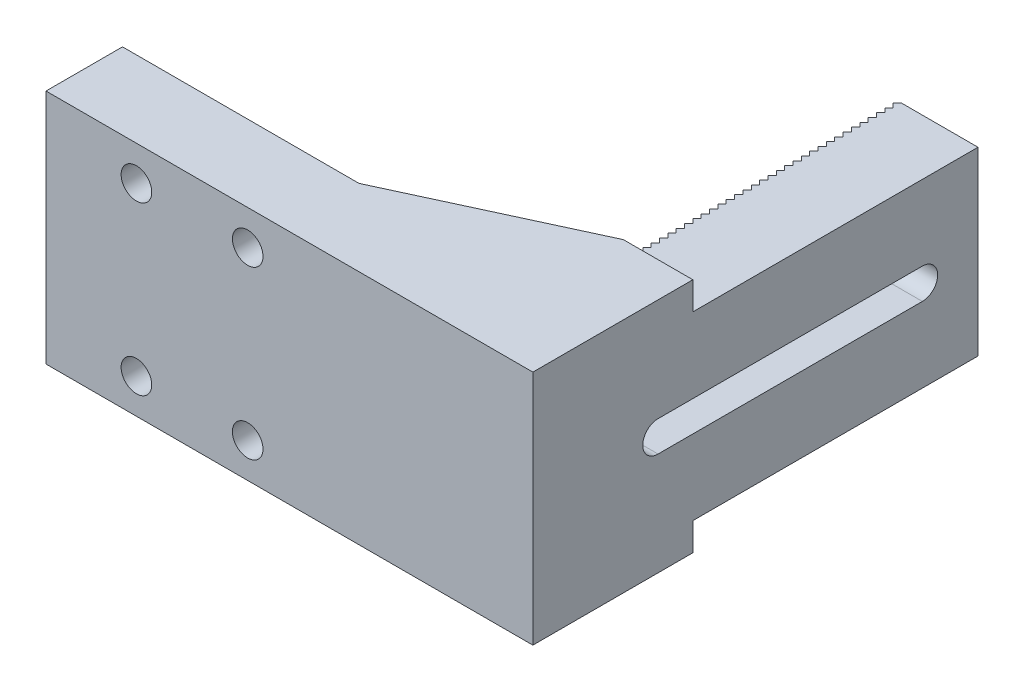
SolidWorks part; units mm, degrees
ref_plane "前视基准面" through (0, 0, 0) normal (0, 0, 1) x (1, 0, 0)
ref_plane "上视基准面" through (0, 0, 0) normal (0, 1, 0) x (1, 0, 0)
ref_plane "右视基准面" through (0, 0, 0) normal (1, 0, 0) x (0, 0, -1)
sketch "草图1" plane through (0, 0, 0) normal (0, 1, 0) x (1, 0, 0)
  line L0 (0, 0) -> (-35, 0)
  line L1 (-35, 0) -> (-35, 5.5)
  line L2 (-35, 5.5) -> (-5, 5.5)
  line L3 (-5, 5.5) -> (-5, 32)
  line L4 (-5, 32) -> (0, 32)
  line L5 (0, 32) -> (0, 0)
  dimension "D1" = 5.5
  dimension "D2" = 5
  dimension "D3" = 35
  dimension "D4" = 32
extrude "凸台-拉伸1" add sketch "草图1" along normal blind 17
sketch "草图4" plane through (0, 0, 0) normal (0, 0, 1) x (1, 0, 0)
  line L0 (-35, 17) -> (-5, 17) construction
  line L1 (-24.5, 27.5741) -> (-24.5, -6.7865) construction
  line L2 (-35, 8.5) -> (-8.9406, 8.5) construction
  line L3 (-35, 17) -> (-35, 0) construction
  line L5 (-5, 17) -> (-5, 0) construction
  circle A0 centre (-28.5, 14.5) radius 1.1
  circle A1 centre (-20.5, 14.5) radius 1.1
  circle A2 centre (-28.5, 2.5) radius 1.1
  circle A3 centre (-20.5, 2.5) radius 1.1
  dimension "D1" = 2.2
  dimension "D2" = 8
  dimension "D3" = 12
  dimension "D5" = 15.5
  dimension "D6" = 2.2
  dimension "D4" = 10.5
extrude "切除-拉伸2" cut sketch "草图4" along direction (0, 0, 1) on the side against the normal through all
sketch "草图8" plane through (-5, 0, 0) normal (-1, 0, 0) x (0, 0, 1)
  line L0 (-32, 15) -> (-11.5, 15)
  line L1 (-32, 17) -> (-32, 0) construction
  line L2 (-11.5, 15) -> (-11.5, 17)
  line L3 (-11.5, 17) -> (-32, 17)
  line L4 (-32, 17) -> (-32, 15)
  line L5 (-32, 8.5) -> (0.3903, 8.5) construction
  line L6 (-11.5, 2) -> (-11.5, 0)
  line L7 (-11.5, 0) -> (-32, 0)
  line L8 (-32, 0) -> (-32, 2)
  line L9 (-32, 2) -> (-11.5, 2)
  line L11 (-32, 17) -> (-5.5, 17) construction
  line L12 (-5.5, 17) -> (-5.5, 0) construction
  point P14 (-11.2961, 15)
  point P15 (-11.2961, 15)
  point P16 (-10.0837, 17)
  point P21 (-10, 15)
  dimension "D2" = 13
  dimension "D3" = 6
extrude "切除-拉伸5" cut sketch "草图8" against normal through all
sketch "草图11" plane through (0, 2, 0) normal (0, -1, 0) x (1, 0, 0)
  line L0 (-5, -5.5) -> (-5, -32)
  line L1 (-5, -32) -> (-5.5, -32)
  line L2 (-5.5, -32) -> (-5.8, -31.7)
  line L3 (-5.8, -31.7) -> (-5.5, -31.4)
  line L29 (-5, -5.5) -> (-35, -5.5) construction
  line L30 (-5.5, -5.5) -> (-5, -5.5)
  line L31 (-5.5, -31.4) -> (-5.8, -31.1)
  line L32 (-5.8, -31.1) -> (-5.5, -30.8)
  line L33 (-5.5, -30.8) -> (-5.8, -30.5)
  line L34 (-5.8, -30.5) -> (-5.5, -30.2)
  line L35 (-5.5, -30.2) -> (-5.8, -29.9)
  line L36 (-5.8, -29.9) -> (-5.5, -29.6)
  line L37 (-5.5, -29.6) -> (-5.8, -29.3)
  line L38 (-5.8, -29.3) -> (-5.5, -29)
  line L39 (-5.5, -29) -> (-5.8, -28.7)
  line L40 (-5.8, -28.7) -> (-5.5, -28.4)
  line L41 (-5.5, -28.4) -> (-5.8, -28.1)
  line L42 (-5.8, -28.1) -> (-5.5, -27.8)
  line L43 (-5.5, -27.8) -> (-5.8, -27.5)
  line L44 (-5.8, -27.5) -> (-5.5, -27.2)
  line L45 (-5.5, -27.2) -> (-5.8, -26.9)
  line L46 (-5.8, -26.9) -> (-5.5, -26.6)
  line L47 (-5.5, -26.6) -> (-5.8, -26.3)
  line L48 (-5.8, -26.3) -> (-5.5, -26)
  line L49 (-5.5, -26) -> (-5.8, -25.7)
  line L50 (-5.8, -25.7) -> (-5.5, -25.4)
  line L51 (-5.5, -25.4) -> (-5.8, -25.1)
  line L52 (-5.8, -25.1) -> (-5.5, -24.8)
  line L53 (-5.5, -24.8) -> (-5.8, -24.5)
  line L54 (-5.8, -24.5) -> (-5.5, -24.2)
  line L55 (-5.5, -24.2) -> (-5.8, -23.9)
  line L56 (-5.8, -23.9) -> (-5.5, -23.6)
  line L57 (-5.5, -23.6) -> (-5.8, -23.3)
  line L58 (-5.8, -23.3) -> (-5.5, -23)
  line L59 (-5.5, -23) -> (-5.8, -22.7)
  line L60 (-5.8, -22.7) -> (-5.5, -22.4)
  line L61 (-5.5, -22.4) -> (-5.8, -22.1)
  line L62 (-5.8, -22.1) -> (-5.5, -21.8)
  line L63 (-5.5, -21.8) -> (-5.8, -21.5)
  line L64 (-5.8, -21.5) -> (-5.5, -21.2)
  line L65 (-5.5, -21.2) -> (-5.8, -20.9)
  line L66 (-5.8, -20.9) -> (-5.5, -20.6)
  line L67 (-5.5, -20.6) -> (-5.8, -20.3)
  line L68 (-5.8, -20.3) -> (-5.5, -20)
  line L69 (-5.5, -20) -> (-5.8, -19.7)
  line L70 (-5.8, -19.7) -> (-5.5, -19.4)
  line L71 (-5.5, -19.4) -> (-5.8, -19.1)
  line L72 (-5.8, -19.1) -> (-5.5, -18.8)
  line L73 (-5.5, -18.8) -> (-5.8, -18.5)
  line L74 (-5.8, -18.5) -> (-5.5, -18.2)
  line L75 (-5.5, -18.2) -> (-5.8, -17.9)
  line L76 (-5.8, -17.9) -> (-5.5, -17.6)
  line L77 (-5.5, -17.6) -> (-5.8, -17.3)
  line L78 (-5.8, -17.3) -> (-5.5, -17)
  line L79 (-5.5, -17) -> (-5.8, -16.7)
  line L80 (-5.8, -16.7) -> (-5.5, -16.4)
  line L81 (-5.5, -16.4) -> (-5.8, -16.1)
  line L82 (-5.8, -16.1) -> (-5.5, -15.8)
  line L83 (-5.5, -15.8) -> (-5.8, -15.5)
  line L84 (-5.8, -15.5) -> (-5.5, -15.2)
  line L85 (-5.5, -15.2) -> (-5.8, -14.9)
  line L86 (-5.8, -14.9) -> (-5.5, -14.6)
  line L87 (-5.5, -14.6) -> (-5.8, -14.3)
  line L88 (-5.8, -14.3) -> (-5.5, -14)
  line L89 (-5.5, -14) -> (-5.8, -13.7)
  line L90 (-5.8, -13.7) -> (-5.5, -13.4)
  line L91 (-5.5, -13.4) -> (-5.8, -13.1)
  line L92 (-5.8, -13.1) -> (-5.5, -12.8)
  line L93 (-5.5, -12.8) -> (-5.8, -12.5)
  line L94 (-5.8, -12.5) -> (-5.5, -12.2)
  line L95 (-5.5, -12.2) -> (-5.8, -11.9)
  line L96 (-5.8, -11.9) -> (-5.5, -11.6)
  line L97 (-5.5, -11.6) -> (-5.8, -11.3)
  line L98 (-5.8, -11.3) -> (-5.5, -11)
  line L99 (-5.5, -11) -> (-5.8, -10.7)
  line L100 (-5.8, -10.7) -> (-5.5, -10.4)
  line L101 (-5.5, -10.4) -> (-5.8, -10.1)
  line L102 (-5.8, -10.1) -> (-5.5, -9.8)
  line L103 (-5.5, -9.8) -> (-5.8, -9.5)
  line L104 (-5.8, -9.5) -> (-5.5, -9.2)
  line L105 (-5.5, -9.2) -> (-5.8, -8.9)
  line L106 (-5.8, -8.9) -> (-5.5, -8.6)
  line L107 (-5.5, -8.6) -> (-5.8, -8.3)
  line L108 (-5.8, -8.3) -> (-5.5, -8)
  line L109 (-5.5, -8) -> (-5.8, -7.7)
  line L110 (-5.8, -7.7) -> (-5.5, -7.4)
  line L111 (-5.5, -7.4) -> (-5.8, -7.1)
  line L112 (-5.8, -7.1) -> (-5.5, -6.8)
  line L113 (-5.5, -6.8) -> (-5.8, -6.5)
  line L114 (-5.8, -6.5) -> (-5.5, -6.2)
  line L115 (-5.5, -6.2) -> (-5.5, -5.5)
  dimension "D1" = 0.5
  dimension "D2" = 135
  dimension "D3" = 0.6
extrude "凸台-拉伸2" add sketch "草图11" against normal up to surface (13 mm away) up to face at (-2.5, 15, -21.75)
sketch "草图6" plane through (-5, 0, 0) normal (-1, 0, 0) x (0, 0, 1)
  line L0 (-39, 8.5) -> (-12.5869, 8.5) construction
  line L2 (-11.5, 17) -> (-5.5, 17) construction
  line L3 (-11.5, 0) -> (-5.5, 0) construction
  line L4 (-28, 8.5) -> (-9, 8.5) construction
  line L5 (-28, 9.6) -> (-9, 9.6)
  line L6 (-28, 7.4) -> (-9, 7.4)
  line L7 (-32, 17) -> (-32, 0) construction
  arc A2 (-28, 9.6) -> (-28, 7.4) centre (-28, 8.5) ccw
  arc A3 (-9, 7.4) -> (-9, 9.6) centre (-9, 8.5) ccw
  point P4 (-18.5, 8.5)
  dimension "D1" = 4
  dimension "D2" = 1.1
  dimension "D3" = 19
extrude "切除-拉伸4" cut sketch "草图6" against normal through all and the other way blind 10
sketch "草图12" plane through (0, 0, 0) normal (0, -1, 0) x (1, 0, 0)
  line L0 (-5, -11.5) -> (-5, -5.5)
  line L1 (-5, -5.5) -> (-18, -5.5)
  line L2 (-5, -5.5) -> (-35, -5.5) construction
  line L3 (-18, -5.5) -> (-5, -11.5)
  dimension "D1" = 13
extrude "凸台-拉伸3" add sketch "草图12" against normal up to surface (2 mm away) up to face at (-5.5098, 2, -18.7793)
sketch "草图13" plane through (0, 17, 0) normal (0, 1, 0) x (1, 0, 0)
  line L0 (-5, 11.5) -> (-5, 5.5)
  line L1 (-5, 5.5) -> (-18, 5.5)
  line L2 (-5, 5.5) -> (-35, 5.5) construction
  line L3 (-18, 5.5) -> (-5.6842, 11.1842) construction
  line L4 (-18, 5.5) -> (-5, 11.5)
extrude "凸台-拉伸4" add sketch "草图13" against normal up to surface (2 mm away) up to face at (-5.5098, 15, -18.7793)
